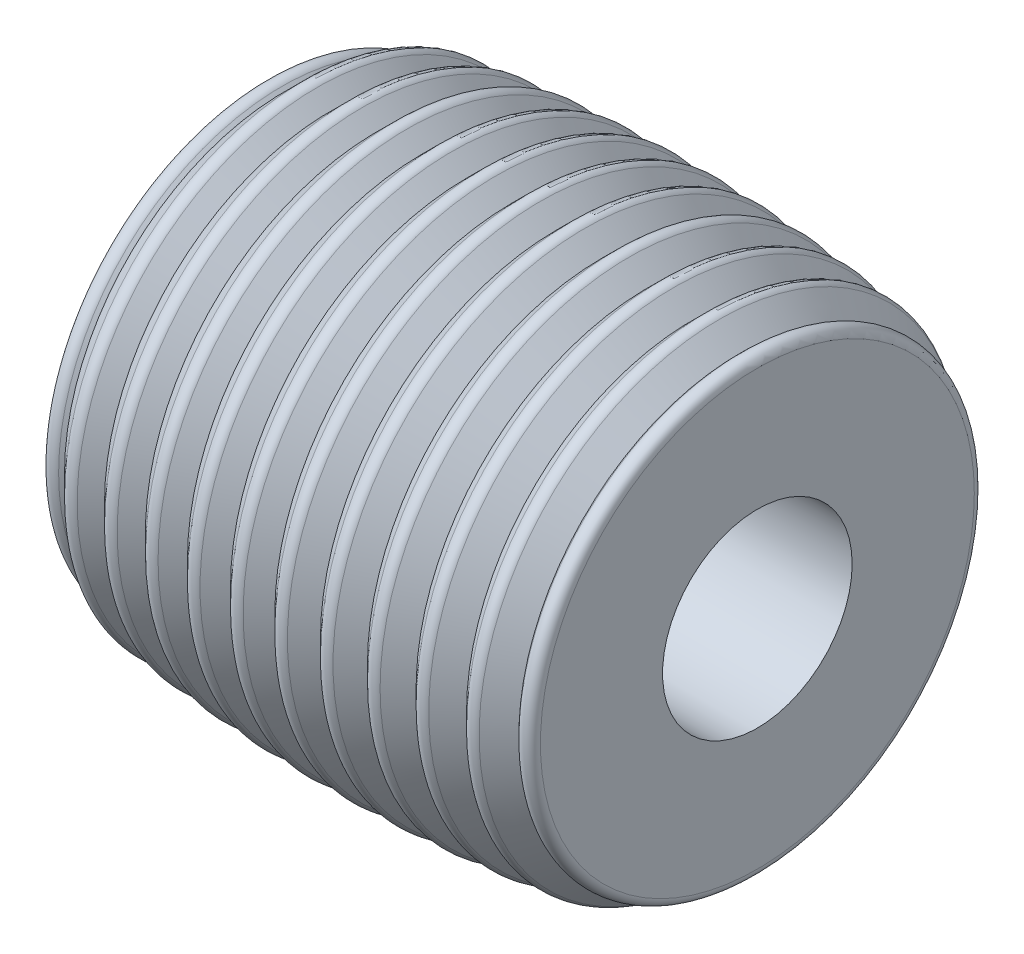
SolidWorks part; units mm, degrees
material "Rubber"
ref_plane "Front Plane" through (0, 0, 0) normal (0, 0, 1) x (1, 0, 0)
ref_plane "Top Plane" through (0, 0, 0) normal (0, 1, 0) x (1, 0, 0)
ref_plane "Right Plane" through (0, 0, 0) normal (1, 0, 0) x (0, 0, -1)
sketch "Sketch2" plane through (0, 0, 0) normal (1, 0, 0) x (0, 0, -1)
  circle A0 centre (0, 0) radius 4.875
  dimension "D1" = 9.75
extrude "Boss-Extrude1" add sketch "Sketch2" against normal mid plane 11
sketch "Sketch5" plane through (0, 0, 0) normal (0, 1, 0) x (1, 0, 0)
  line L0 (5.5, 4.875) -> (-5.5, 4.875) construction
  line L1 (-5.5, 4.875) -> (0, 0)
  line L2 (0, 0) -> (5.5, 4.875)
  line L3 (0, -0.6681) -> (6.6056, 5.1868) construction
  line L4 (-6.6056, 5.1868) -> (0, -0.6681)
  line L5 (-0.4965, 5.8138) -> (-1.0077, 5.3026)
  line L6 (0.4965, 5.8138) -> (1.0077, 5.3026)
  line L7 (1.0077, 5.3026) -> (1.4906, 5.7855)
  line L10 (-1.0077, 5.3026) -> (-1.4906, 5.7855)
  line L11 (-1.4906, 5.7855) -> (-2.018, 5.2581)
  line L13 (0, 5.3173) -> (0.4965, 5.8138)
  line L14 (0, 5.3173) -> (-0.4965, 5.8138)
  line L15 (1.4906, 5.7855) -> (2.018, 5.2581)
  line L16 (2.018, 5.2581) -> (2.4884, 5.7285)
  line L17 (2.4884, 5.7285) -> (3.0336, 5.1834)
  line L18 (3.0336, 5.1834) -> (3.4925, 5.6422)
  line L19 (3.4925, 5.6422) -> (4.0574, 5.0773)
  line L20 (4.0574, 5.0773) -> (4.5054, 5.5254)
  line L21 (4.5054, 5.5254) -> (5.0924, 4.9385)
  line L22 (5.0924, 4.9385) -> (5.5, 5.3461)
  line L23 (5.5, 4.875) -> (5.5, 5.3461)
  line L24 (-2.018, 5.2581) -> (-2.4884, 5.7285)
  line L25 (-2.4884, 5.7285) -> (-3.0336, 5.1834)
  line L26 (-3.0336, 5.1834) -> (-3.4925, 5.6422)
  line L27 (-3.4925, 5.6422) -> (-4.0574, 5.0773)
  line L28 (-4.0574, 5.0773) -> (-4.5054, 5.5254)
  line L29 (-4.5054, 5.5254) -> (-5.0924, 4.9385)
  line L30 (-5.0924, 4.9385) -> (-5.5, 5.3461)
  line L31 (-5.5, 5.3461) -> (-5.5, 4.875)
  line L32 (-5.5, 4.875) -> (5.5, 4.875)
  line L33 (5.5, 0) -> (-5.5, 0)
  line L34 (5.5, -4.875) -> (5.5, 4.875) construction
  line L35 (-5.5, 4.875) -> (-5.5, -4.875) construction
  arc A0 (-5.5, 4.875) -> (5.5, 4.875) centre (0, -29.0977) cw construction
  arc A1 (-6.6056, 5.1868) -> (6.6056, 5.1868) centre (0, -29.0977) cw construction
  point P6 (0, 5.3173)
  dimension "D2" = 0.5
  dimension "D1" = 34.415
sketch "Sketch6" plane through (5.5, 0, 0) normal (1, 0, 0) x (0, 0, -1)
  point P0 (0, 0)
revolve "Revolve1" add sketch "Sketch5" angle 360 about L33
sketch "Sketch4" plane through (5.5, 0, 0) normal (1, 0, 0) x (0, 0, -1)
  circle A0 centre (0, 0) radius 2.125
  dimension "D1" = 4.25
extrude "Cut-Extrude1" cut sketch "Sketch4" against normal up to next
fillet "Fillet1" radius 0.2 12 edges at (3.4925, 0, -5.6422) (2.4884, 0, -5.7285) (4.5054, 0, -5.5254) (5.5, 0, -5.3461) (1.4906, 0, -5.7855) (0.4965, 0, -5.8138) (-0.4965, 0, -5.8138) (-1.4906, 0, -5.7855) (-2.4884, 0, -5.7285) (-3.4925, 0, -5.6422) (-4.5054, 0, -5.5254) (-5.5, 0, -5.3461)
